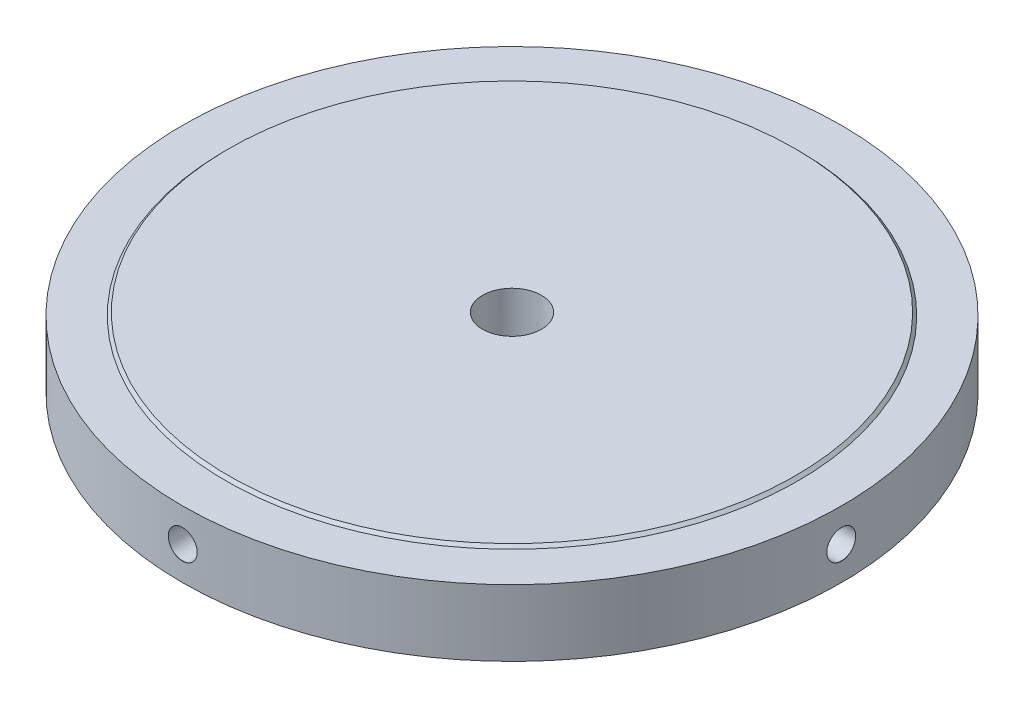
SolidWorks part; units mm, degrees
material "PETG"
ref_plane "Front Plane" through (0, 0, 0) normal (0, 0, 1) x (1, 0, 0)
ref_plane "Top Plane" through (0, 0, 0) normal (0, 1, 0) x (1, 0, 0)
ref_plane "Right Plane" through (0, 0, 0) normal (1, 0, 0) x (0, 0, -1)
sketch "Sketch1" plane through (0, 0, 0) normal (0, 0, 1) x (1, 0, 0)
  line L0 (0, 0) -> (0, 50000) construction
  line L1 (0, 6.25) -> (49, 6.25)
  line L3 (0, 6.25) -> (0, -5.75)
  line L4 (0, -5.75) -> (57, -5.75)
  line L5 (57, 5.75) -> (57, -5.75)
  line L7 (57, 5.75) -> (49.5, 5.75)
  line L10 (49, 6.25) -> (49.5, 5.75)
  point P7 (57, 0)
  dimension "D1" = 11.5
  dimension "D2" = 114
  dimension "D3" = 98
  dimension "D4" = 0.5
  dimension "D5" = 0.5
revolve "Revolve1" add sketch "Sketch1" angle 360 about L0
hole_wizard "Ø5.0mm Dowel Hole1" positions "3DSketch1" profile "Sketch2" hole size "Ø5.0" standard "ISO"
sketch3d "3DSketch1"
  circle A0 centre (0, 0, 0) radius 57 construction
  point P0 (57, 0, 0)
  point P2 (0, 0, 57)
  point P4 (-57, 0, 0)
  point P6 (0, 0, -57)
  point P11 (0, 57, 0)
sketch "Sketch2" plane through (57, 0, 0) normal (0, 1, 0) x (0, 0, -1)
  line L0 (0, 0) -> (0, 13.5022)
  line L1 (0, 13.5022) -> (2.5, 12)
  line L2 (2.5, 12) -> (2.5, 0.025)
  line L3 (2.5, 0.025) -> (2.525, 0)
  line L5 (2.525, 0) -> (0, 0)
  line L6 (-2.5, 0.025) -> (-2.525, 0) construction
  line L10 (0, 13.5022) -> (-2.5, 12) construction
  line L11 (0, -6.35) -> (0, 107.95) construction
  dimension "Hole Dia." = 5
  dimension "Hole Depth" = 12
  dimension "Near C'Sink Dia." = 5.05
  dimension "Near C'Sink Angle" = 90
  dimension "Drill Angle" = 118
hole_wizard "M12 Tapped Hole1" positions "Sketch3" profile "Sketch4" tap size "M12" standard "ISO" end condition up to next
sketch "Sketch3" plane through (0, 6.25, 0) normal (0, 1, 0) x (1, 0, 0)
  point P2 (0, 0)
sketch "Sketch4" plane through (0, 6.25, 0) normal (1, 0, 0) x (0, 0, 1)
  line L0 (0, 0) -> (0, 12)
  line L1 (0, 12) -> (5.1, 12)
  line L2 (5.1, 12) -> (5.1, 0)
  line L5 (5.1, 0) -> (0, 0)
  line L11 (0, -6.35) -> (0, 107.95) construction
  dimension "Thru Tap Drill Dia." = 10.2
  dimension "Thru Tap Drill Depth" = 12
cosmetic thread "Hole Thread10" parameters "D2"=12
equation "\"CanSat_Len\"= 400mm"
equation "\"CanSat_Dia\"= 150mm"
equation "\"BodyTube_ID\"= 114mm"
equation "\"BodyTube_OD\"= 120mm"
equation "\"PayLoadBay_ID\"= 164mm"
equation "\"PayLoadBay_OD\"= 170mm"
equation "\"ParachuteBay_Pitch\"= 300mm"
equation "\"ElectronicsTray_PitchDist\"= 50mm"
equation "\"ElectronicsTray_Height\"= 140mm"
equation "\"D2@Sketch1\"=\"BodyTube_ID\""
